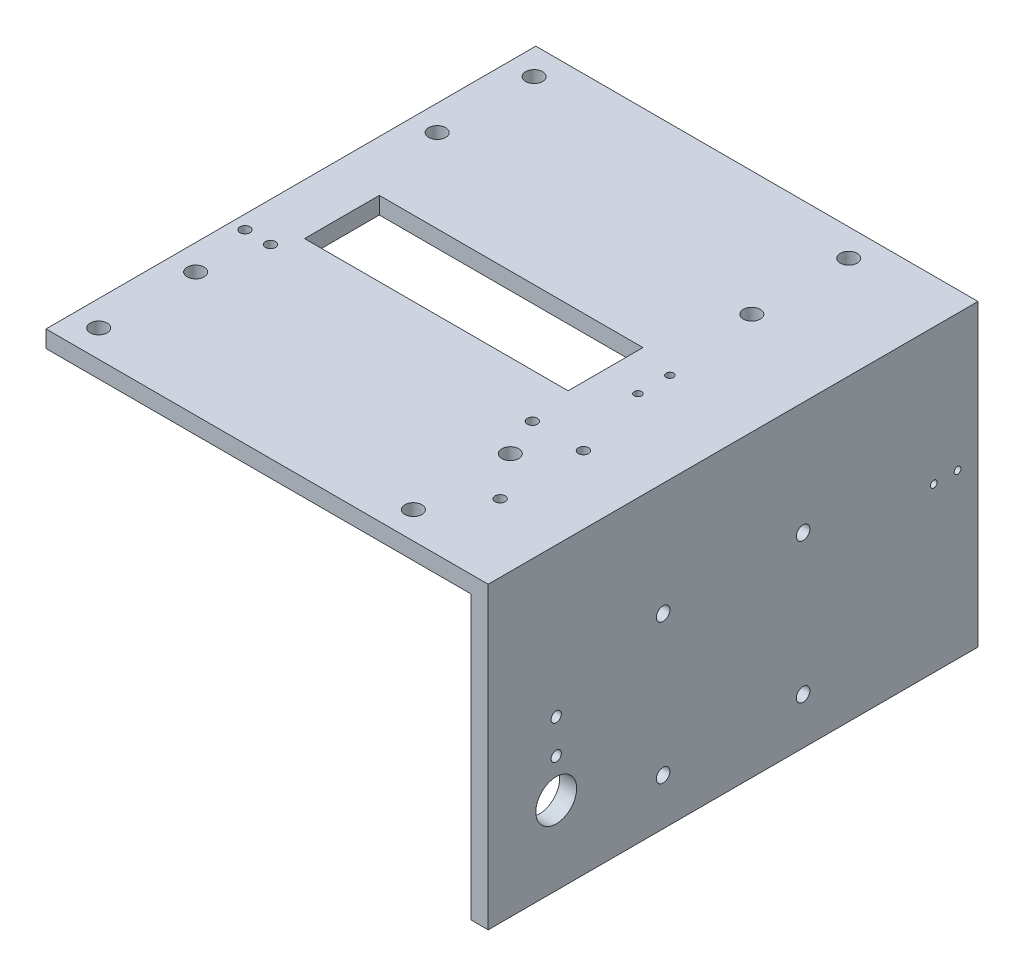
SolidWorks part; units mm, degrees
ref_plane "Front Plane" through (0, 0, 0) normal (0, 0, 1) x (1, 0, 0)
ref_plane "Top Plane" through (0, 0, 0) normal (0, 1, 0) x (1, 0, 0)
ref_plane "Right Plane" through (0, 0, 0) normal (1, 0, 0) x (0, 0, -1)
sketch "Croquis1" plane through (0, 0, 0) normal (0, 1, 0) x (1, 0, 0)
  line L1 (-7.5, -72) -> (7.5, -72)
  line L2 (-7.5, -72) -> (-7.5, 72)
  line L3 (-7.5, 72) -> (7.5, 72)
  line L4 (7.5, -72) -> (7.5, 72)
  point P4 (0, -72)
  point P6 (7.5, 0)
  dimension "D1" = 144
  dimension "D2" = 15
extrude "Saliente-Extruir1" add sketch "Croquis1" along normal mid plane 92.5
sketch "Croquis2" plane through (0, 46.25, 0) normal (0, -1, 0) x (1, 0, 0)
  line L1 (-122.5, 72) -> (-22.5, 72)
  line L2 (-122.5, 72) -> (-122.5, -72)
  line L3 (-122.5, -72) -> (-22.5, -72)
  line L5 (-122.5, 72) -> (-22.5, -72) construction
  line L6 (-122.5, -72) -> (-22.5, 72) construction
  line L9 (-22.5, -72) -> (7.5, -72)
  line L10 (7.5, -72) -> (7.5, 72)
  line L11 (7.5, 72) -> (-22.5, 72)
  line L12 (-7.5, -72) -> (-7.5, 72) construction
  point P0 (-72.5, 0)
  dimension "D2" = 100
  dimension "D3" = 144
  dimension "D4" = 100
  dimension "D5" = 115
extrude "Saliente-Extruir2" add sketch "Croquis2" against normal mid plane 15
sketch "Croquis4" plane through (0, 53.75, 0) normal (0, 1, 0) x (1, 0, 0)
  line L0 (-122.5, -72) -> (-122.5, 72) construction
  line L1 (-30, -11) -> (-107.5, -11)
  line L2 (-30, -11) -> (-30, 11)
  line L3 (-30, 11) -> (-107.5, 11)
  line L4 (-107.5, -11) -> (-107.5, 11)
  line L5 (-30, -11) -> (-107.5, 11) construction
  line L6 (-30, 11) -> (-107.5, -11) construction
  point P0 (-68.75, 0)
  point P6 (-30, 0)
  dimension "D1" = 22
  dimension "D2" = 77.5
  dimension "D3" = 15
extrude "Cortar-Extruir2" cut sketch "Croquis4" against normal blind 30
sketch "Croquis5" plane through (0, 53.75, 0) normal (0, 1, 0) x (1, 0, 0)
  line L2 (-68.75, 62.5) -> (-68.75, -66.5758) construction
  line L6 (-107.5, 0) -> (-30, 0) construction
  line L7 (-107.5, 11) -> (-107.5, -11) construction
  line L8 (-30, -11) -> (-30, 11) construction
  line L10 (7.5, 72) -> (7.5, -72) construction
  line L12 (7.5, -72) -> (-122.5, -72) construction
  circle A0 centre (-115, -64) radius 2.5
  circle A1 centre (-115, -35.5) radius 2.5
  circle A2 centre (-22.5, -35.5) radius 2.5
  circle A3 centre (-22.5, -64) radius 2.5
  circle A8 centre (-22.5, 64) radius 2.5
  circle A9 centre (-22.5, 35.5) radius 2.5
  circle A10 centre (-115, 35.5) radius 2.5
  circle A11 centre (-115, 64) radius 2.5
  dimension "D1" = 5
  dimension "D2" = 5
  dimension "D3" = 28.5
  dimension "D4" = 8
  dimension "D5" = 115
  dimension "D6" = 30
sketch "Croquis3" plane through (-7.5, 0, 0) normal (-1, 0, 0) x (0, 0, 1)
  line L3 (-72, 53.75) -> (72, 53.75) construction
  line L4 (72, 53.75) -> (72, -46.25) construction
  circle A4 centre (52, -11.25) radius 6
  dimension "D11" = 12
  dimension "D9" = 65
  dimension "D10" = 20
extrude "Cortar-Extruir1" cut sketch "Croquis3" against normal blind 15
extrude "Cortar-Extruir4" cut sketch "Croquis5" against normal blind 35
sketch "Croquis7" plane through (0, 53.75, 0) normal (0, 1, 0) x (1, 0, 0)
  line L0 (-30, -11) -> (-30, 11) construction
  line L1 (-19, 9) -> (-19, -11) construction
  circle A0 centre (-19, 7.9) radius 1.1
  circle A1 centre (-19, -1.48) radius 1.1
  dimension "D1" = 2.2
  dimension "D2" = 2.2
  dimension "D3" = 11
  dimension "D4" = 9.38
  dimension "D5" = 20
extrude "Cortar-Extruir6" cut sketch "Croquis7" against normal blind 25
sketch "Croquis8" plane through (-7.5, 0, 0) normal (-1, 0, 0) x (0, 0, 1)
  line L0 (72, 38.75) -> (72, -46.25) construction
  line L1 (-72, -46.25) -> (72, -46.25)
  line L2 (-72, -46.25) -> (-72, -34.25)
  line L3 (-72, -34.25) -> (72, -34.25)
  line L4 (72, -46.25) -> (72, -34.25)
  dimension "D1" = 12
extrude "Cortar-Extruir7" cut sketch "Croquis8" against normal blind 50
sketch "Croquis9" plane through (0, 0, 72) normal (0, 0, 1) x (1, 0, 0)
  line L6 (-7.5, -34.25) -> (-7.5, 38.75)
  line L7 (-7.5, 38.75) -> (-122.5, 38.75)
  line L8 (-7.5, -34.25) -> (-2.5, -34.25)
  line L9 (7.5, -34.25) -> (-7.5, -34.25) construction
  line L10 (-2.5, -34.25) -> (-2.5, 43.75)
  line L11 (-122.5, 38.75) -> (-122.5, 43.75)
  line L12 (-122.5, 53.75) -> (-122.5, 38.75) construction
  line L13 (-122.5, 43.75) -> (-2.5, 43.75)
  line L14 (7.5, 53.75) -> (7.5, -34.25) construction
  line L15 (7.5, 53.75) -> (-122.5, 53.75) construction
  dimension "D1" = 10
  dimension "D2" = 10
extrude "Cortar-Extruir8" cut sketch "Croquis9" against normal blind 190
sketch "Croquis10" plane through (-2.5, 0, 0) normal (-1, 0, 0) x (0, 0, 1)
  line L0 (0, 0) -> (-38.575, 0) construction
  line L1 (-38.575, 0) -> (-38.575, 38.575) construction
  line L2 (-38.575, 38.575) -> (38.575, 38.575) construction
  line L3 (38.575, 38.575) -> (38.575, -38.575) construction
  line L4 (38.575, -38.575) -> (-38.575, -38.575) construction
  line L5 (-38.575, -38.575) -> (-38.575, 0) construction
  circle A0 centre (-20.575, -20.575) radius 2
  circle A1 centre (-20.575, 20.575) radius 2
  circle A2 centre (20.575, 20.575) radius 2
  circle A3 centre (20.575, -20.575) radius 2
  point P6 (0, -38.575)
  dimension "D4" = 4
  dimension "D6" = 18
  dimension "D8" = 18
  dimension "D9" = 4
  dimension "D12" = 4
  dimension "D13" = 4
  dimension "D14" = 18
  dimension "D15" = 18
  dimension "D1" = 38.575
  dimension "D2" = 38.575
  dimension "D3" = 77.15
  dimension "D5" = 18
  dimension "D7" = 18
  dimension "D10" = 18
  dimension "D11" = 18
extrude "Cortar-Extruir9" cut sketch "Croquis10" against normal blind 10
sketch "Croquis12" plane through (0, 43.75, 0) normal (0, -1, 0) x (1, 0, 0)
  line L0 (-2.5, -72) -> (-2.5, 72) construction
  line L1 (-2.5, 72) -> (-122.5, 72) construction
  circle A0 centre (-12.5, 48.5) radius 1.5
  circle A1 centre (-12.5, 24) radius 1.5
  circle A4 centre (-27.5, 24) radius 1.5
  dimension "D4" = 24.5
  dimension "D6" = 15
  dimension "D9" = 3
  dimension "D10" = 3
  dimension "D5" = 3
  dimension "D1" = 10
  dimension "D2" = 23.5
  dimension "D3" = 10
extrude "Cortar-Extruir11" cut sketch "Croquis12" against normal blind 10
sketch "Croquis13" plane through (0, 53.75, 0) normal (0, 1, 0) x (1, 0, 0)
  line L2 (-107.5, -11) -> (-107.5, -17.5) construction
  line L3 (-107.5, -17.5) -> (-111, -17.5) construction
  line L4 (-122.5, -72) -> (-122.5, 72) construction
  circle A1 centre (-111, -17.5) radius 1.5
  circle A2 centre (-118.5, -17.5) radius 1.5
  dimension "D6" = 3
  dimension "D7" = 3
  dimension "D4" = 6.5
  dimension "D5" = 3.5
  dimension "D8" = 4
  dimension "D9" = 6.5
extrude "Cortar-Extruir12" cut sketch "Croquis13" against normal blind 10
sketch "Croquis14" plane through (0, 0, 72) normal (0, 0, 1) x (1, 0, 0)
  line L0 (2.5, -34.25) -> (2.5, 48.75)
  line L1 (7.5, -34.25) -> (-2.5, -34.25) construction
  line L2 (2.5, 48.75) -> (-126.1912, 48.75)
  line L3 (-126.1912, 48.75) -> (-126.1912, 43.75)
  line L4 (-126.1912, 43.75) -> (-2.5, 43.75)
  line L5 (-2.5, 43.75) -> (-2.5, -34.25)
  line L6 (-2.5, -34.25) -> (2.5, -34.25)
  dimension "D1" = 5
  dimension "D2" = 5
extrude "Cortar-Extruir13" cut sketch "Croquis14" against normal blind 190
sketch "Croquis15" plane through (7.5, 0, 0) normal (1, 0, 0) x (0, 0, -1)
  line L0 (-52, -5.25) -> (-52, 15.4395) construction
  circle A0 centre (-52, -11.25) radius 6 construction
  circle A1 centre (-52, 0) radius 1.5
  circle A2 centre (-52, 10) radius 1.5
  dimension "D3" = 3
  dimension "D4" = 3
  dimension "D1" = 5.25
  dimension "D2" = 10
extrude "Cortar-Extruir14" cut sketch "Croquis15" against normal blind 10
sketch "Croquis16" plane through (7.5, 0, 0) normal (1, 0, 0) x (0, 0, -1)
  line L0 (54, 5.6505) -> (54, 23.2523) construction
  line L1 (72, 53.75) -> (72, -34.25) construction
  line L2 (72, 53.75) -> (-72, 53.75) construction
  circle A0 centre (59, 13.75) radius 1
  circle A1 centre (66, 13.75) radius 1
  dimension "D1" = 2
  dimension "D2" = 2
  dimension "D3" = 18
  dimension "D4" = 5
  dimension "D5" = 6
  dimension "D6" = 40
  dimension "D7" = 40
extrude "Cortar-Extruir15" cut sketch "Croquis16" against normal blind 10
